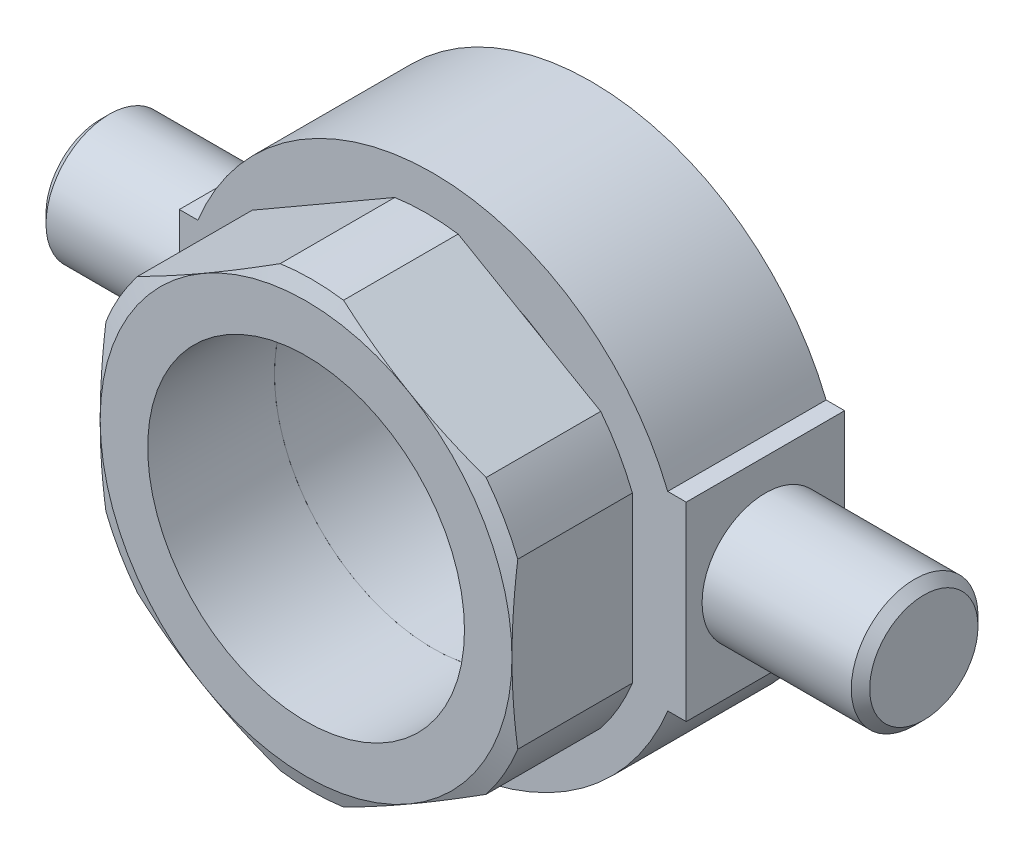
SolidWorks part; units mm, degrees
ref_plane "前视基准面" through (0, 0, 0) normal (0, 0, 1) x (1, 0, 0)
ref_plane "上视基准面" through (0, 0, 0) normal (0, 1, 0) x (1, 0, 0)
ref_plane "右视基准面" through (0, 0, 0) normal (1, 0, 0) x (0, 0, -1)
sketch "草图1" plane through (0, 0, 0) normal (0, 0, 1) x (1, 0, 0)
  line L0 (-26, 0) -> (26, 0) construction
  line L1 (0, 6) -> (0, -6) construction
  line L2 (0, 14) -> (0, -14) construction
  line L3 (0, 15.0111) -> (-13, 7.5056)
  line L4 (-13, 7.5056) -> (-13, -7.5056)
  line L5 (-13, -7.5056) -> (0, -15.0111)
  line L6 (0, -15.0111) -> (13, -7.5056)
  line L7 (13, -7.5056) -> (13, 7.5056)
  line L8 (13, 7.5056) -> (0, 15.0111)
  line L9 (0, 0) -> (10, 0) construction
  line L10 (0, 0) -> (-8, 0) construction
  circle A0 centre (0, 0) radius 16
  circle A1 centre (0, 0) radius 13 construction
  circle A2 centre (0, 0) radius 12.5
  circle A3 centre (0, 0) radius 10
  point P18 (0, 4)
  dimension "BJ" = 32
  dimension "CA" = 26
  dimension "CD" = 25
  dimension "CE" = 20
  dimension "BF" = 52
  dimension "BH" = 12
  dimension "CB" = 28
  dimension "BG" = 8
  dimension "BB" = 10
  dimension "CC" = 8
sketch "草图2" plane through (0, 0, 0) normal (0, 0, 1) x (1, 0, 0)
  line L0 (-16, 6) -> (-16, -6)
  line L1 (0, 0) -> (0, 4) construction
  line L2 (16, 6) -> (16, -6)
  line L3 (-16, 6) -> (-14.8324, 6)
  line L4 (-16, -6) -> (-14.8324, -6)
  line L5 (16, 6) -> (14.8324, 6)
  line L6 (16, -6) -> (14.8324, -6)
  circle A0 centre (0, 0) radius 16 construction
  arc A1 (-14.8324, -6) -> (14.8324, -6) centre (0, 0) ccw
  arc A2 (14.8324, 6) -> (-14.8324, 6) centre (0, 0) ccw
extrude "凸台-拉伸1" add sketch "草图2" along normal blind 10
sketch "草图3" plane through (-16, 0, 0) normal (-1, 0, 0) x (0, 0, 1)
  line L0 (5, 6) -> (5, -6) construction
  line L1 (10, 6) -> (0, 6) construction
  line L2 (10, -6) -> (0, -6) construction
  circle A0 centre (5, 0) radius 4
  point P8 (5, 4)
extrude "凸台-拉伸2" add sketch "草图3" along normal up to vertex (10 mm away) up to point (-26, 0, 0)
mirror "镜向1" about plane through (0, 0, 0) normal (1, 0, 0) of "凸台-拉伸2"
sketch "草图4" plane through (0, 0, 10) normal (0, 0, 1) x (1, 0, 0)
  line L0 (13, 7.5056) -> (0, 15.0111) construction
  line L1 (13, -7.5056) -> (13, 7.5056) construction
  line L2 (0, -15.0111) -> (13, -7.5056) construction
  line L3 (-13, -7.5056) -> (0, -15.0111) construction
  line L4 (-13, 7.5056) -> (-13, -7.5056) construction
  line L5 (0, 15.0111) -> (-13, 7.5056) construction
  line L6 (13, 7.5056) -> (0, 15.0111)
  line L7 (13, -7.5056) -> (13, 7.5056)
  line L8 (0, -15.0111) -> (13, -7.5056)
  line L9 (-13, -7.5056) -> (0, -15.0111)
  line L10 (-13, 7.5056) -> (-13, -7.5056)
  line L11 (0, 15.0111) -> (-13, 7.5056)
extrude "凸台-拉伸3" add sketch "草图4" along normal blind 8 separate body
sketch "草图5" plane through (0, 0, 0) normal (0, 1, 0) x (1, 0, 0)
  line L0 (-13, -18) -> (-23.9899, -18)
  line L1 (-13, -18) -> (-23.9899, -14)
  line L2 (-13, -14) -> (0, -14) construction
  line L3 (-13, -18) -> (-13, -10) construction
  line L4 (0, -18) -> (0, -10) construction
  line L5 (-23.9899, -18) -> (-23.9899, -14)
  dimension "D1" = 20
revolve "切除-旋转1" cut sketch "草图5" angle 360 about axis through (0, 0, 10) along (0, 0, -1)
sketch "草图6" plane through (0, 0, 10) normal (0, 0, 1) x (1, 0, 0)
  circle A0 centre (0, 0) radius 15.0111
  circle A1 centre (0, 0) radius 12.5 construction
  circle A2 centre (0, 0) radius 12.5
extrude "切除-拉伸1" cut sketch "草图6" along normal blind 0.4
sketch "草图7" plane through (0, 0, 18) normal (0, 0, -1) x (-1, 0, 0)
  circle A0 centre (0, 0) radius 14
extrude "切除-拉伸2" cut sketch "草图7" along normal up to surface (8 mm away) flip side to cut up to face at (0, 0, 10)
sketch "草图8" plane through (0, 0, 0) normal (0, 0, -1) x (-1, 0, 0)
  circle A0 centre (0, 0) radius 10 construction
  circle A1 centre (0, 0) radius 10
extrude "切除-拉伸3" cut sketch "草图8" against normal through all
sketch "草图9" plane through (0, 0, 18) normal (0, 0, 1) x (1, 0, 0)
  circle A0 centre (0, 0) radius 10 construction
  circle A1 centre (0, 0) radius 10
extrude "切除-拉伸4" cut sketch "草图9" against normal through all
cosmetic thread "装饰螺纹线1" parameters "D2"=20.1
chamfer "倒角1" distance 0.58 angle 45 2 edges at (26, 0, 9) (-26, 0, 9)
equation "\"D1@凸台-拉伸3\" = \"CC@草图1\""
equation "\"D1@凸台-拉伸1\" = \"BB@草图1\""
equation "\"D1@切除-拉伸1\" = \"CC@草图1\"*0.05"
equation "\"D2@装饰螺纹线1\" = \"CE@草图1\"+0.1"
equation "\"D1@倒角1\" = \"BG@草图1\"/100+0.5"
